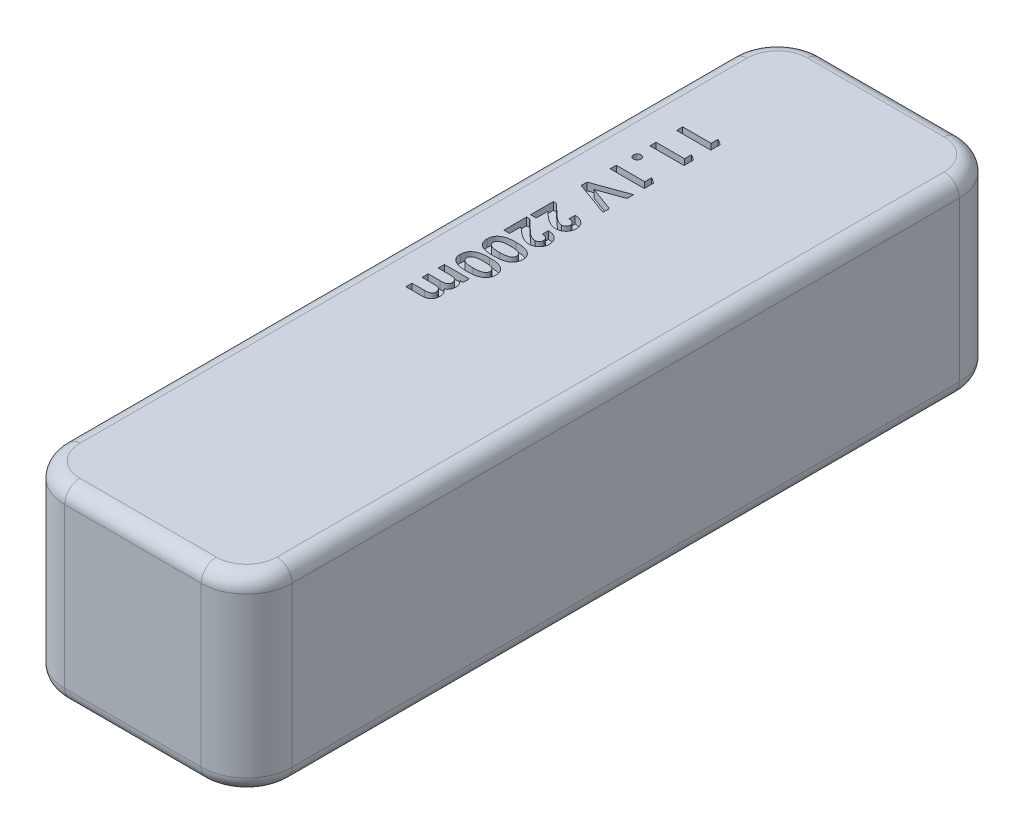
SolidWorks part; units mm, degrees
ref_plane "前基準面" through (0, 0, 0) normal (0, 0, 1) x (1, 0, 0)
ref_plane "上基準面" through (0, 0, 0) normal (0, 1, 0) x (1, 0, 0)
ref_plane "右基準面" through (0, 0, 0) normal (1, 0, 0) x (0, 0, -1)
sketch "草圖1" plane through (0, 0, 0) normal (0, 1, 0) x (1, 0, 0)
  line L1 (-15, -50) -> (15, -50)
  line L2 (-15, -50) -> (-15, 50)
  line L3 (-15, 50) -> (15, 50)
  line L4 (15, -50) -> (15, 50)
  line L5 (-15, -50) -> (15, 50) construction
  line L6 (-15, 50) -> (15, -50) construction
  point P0 (0, 0)
  dimension "D1" = 30
  dimension "D2" = 100
extrude "填料-伸長1" add sketch "草圖1" along normal blind 25
fillet "圓角2" radius 6 4 edges at (-15, 12.5, -50) (15, 12.5, -50) (-15, 12.5, 50) (15, 12.5, 50)
fillet "圓角3" radius 2 16 edges at (13.2426, 25, -48.2426) (15, 25, 0) (13.2426, 25, 48.2426) (0, 25, 50) (-13.2426, 25, 48.2426) (-15, 25, 0) (-13.2426, 25, -48.2426) (0, 25, -50) (-13.2426, 0, 48.2426) (0, 0, 50) (13.2426, 0, 48.2426) (15, 0, 0) (13.2426, 0, -48.2426) (0, 0, -50) (-13.2426, 0, -48.2426) (-15, 0, 0)
sketch "草圖2" plane through (0, 25, 0) normal (0, 1, 0) x (1, 0, 0)
  line L0 (-9.3816, 33.3473) -> (-9.3816, -2.8145) construction
  text T0 "11.1V 2200mah" font "Century Gothic" height 4.5
extrude "除料-伸長1" cut sketch "草圖2" against normal blind 1
